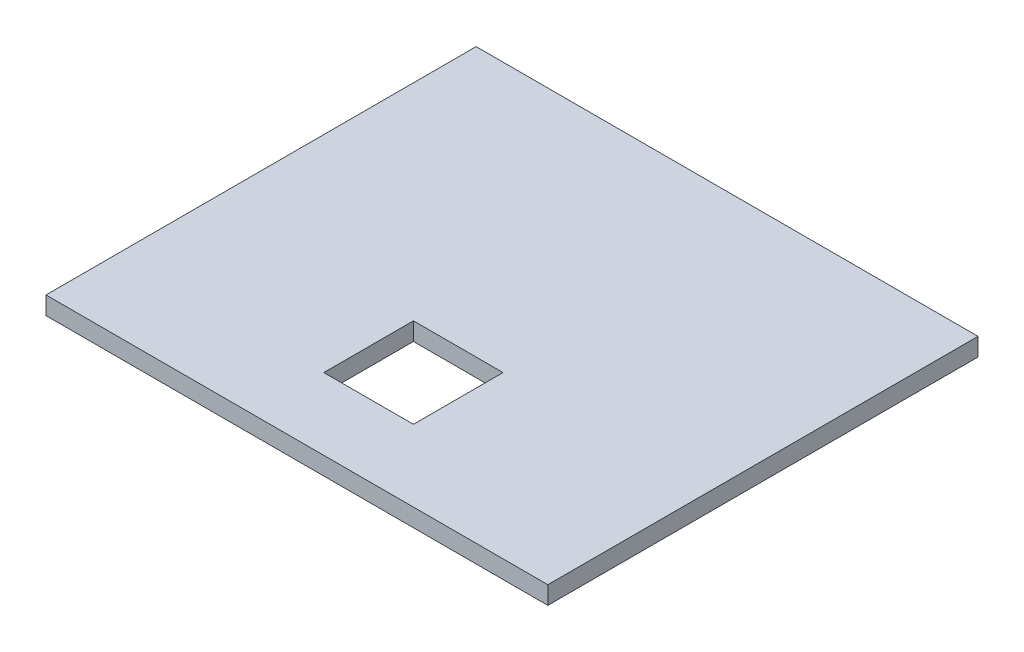
SolidWorks part; units mm, degrees
material "Oak"
ref_plane "Front Plane" through (0, 0, 0) normal (0, 0, 1) x (1, 0, 0)
ref_plane "Top Plane" through (0, 0, 0) normal (0, 1, 0) x (1, 0, 0)
ref_plane "Right Plane" through (0, 0, 0) normal (1, 0, 0) x (0, 0, -1)
sketch "Sketch1" plane through (0, 0, 0) normal (0, 1, 0) x (1, 0, 0)
  line L1 (-88.9, -76.2) -> (88.9, -76.2)
  line L2 (-88.9, -76.2) -> (-88.9, 76.2)
  line L3 (-88.9, 76.2) -> (88.9, 76.2)
  line L4 (88.9, -76.2) -> (88.9, 76.2)
  line L5 (-88.9, -76.2) -> (88.9, 76.2) construction
  line L6 (-88.9, 76.2) -> (88.9, -76.2) construction
  point P0 (0, 0)
  dimension "D1" = 152.4
  dimension "D2" = 177.8
extrude "Boss-Extrude1" add sketch "Sketch1" along normal blind 6.35
sketch "Sketch2" plane through (0, 6.35, 0) normal (0, 1, 0) x (1, 0, 0)
  line L0 (88.9, -76.2) -> (88.9, 76.2) construction
  line L2 (-88.9, -76.2) -> (88.9, -76.2) construction
  line L3 (-15.875, -19.05) -> (15.875, -19.05)
  line L4 (-15.875, -19.05) -> (-15.875, -50.8)
  line L5 (-15.875, -50.8) -> (15.875, -50.8)
  line L6 (15.875, -19.05) -> (15.875, -50.8)
  line L7 (-15.875, -19.05) -> (15.875, -50.8) construction
  line L8 (-15.875, -50.8) -> (15.875, -19.05) construction
  dimension "D1" = 31.75
  dimension "D2" = 31.75
  dimension "D3" = 73.025
  dimension "D4" = 25.4
extrude "Cut-Extrude1" cut sketch "Sketch2" against normal through all
